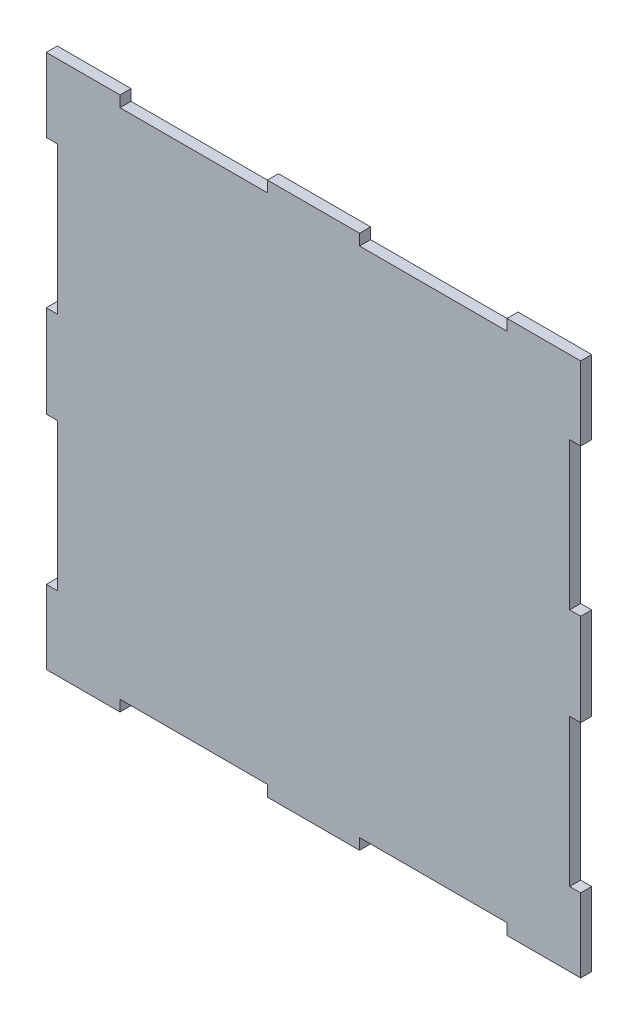
SolidWorks part; units mm, degrees
ref_plane "Front Plane" through (0, 0, 0) normal (0, 0, 1) x (1, 0, 0)
ref_plane "Top Plane" through (0, 0, 0) normal (0, 1, 0) x (1, 0, 0)
ref_plane "Right Plane" through (0, 0, 0) normal (1, 0, 0) x (0, 0, -1)
sketch "Sketch1" plane through (0, 0, 0) normal (0, 0, 1) x (1, 0, 0)
  line L1 (-72.5, 72.5) -> (72.5, 72.5)
  line L2 (-72.5, 72.5) -> (-72.5, -72.5)
  line L3 (-72.5, -72.5) -> (72.5, -72.5)
  line L4 (72.5, 72.5) -> (72.5, -72.5)
  line L5 (-72.5, 72.5) -> (72.5, -72.5) construction
  line L6 (-72.5, -72.5) -> (72.5, 72.5) construction
  point P0 (0, 0)
  dimension "D1" = 145
  dimension "D2" = 145
extrude "Boss-Extrude179" add sketch "Sketch1" along normal blind 3
sketch "Sketch2" plane through (0, 0, 3) normal (0, 0, 1) x (1, 0, 0)
  line L0 (-72.5, 0) -> (0, 0) construction
  line L1 (-72.5, 72.5) -> (-72.5, -72.5) construction
  line L2 (0, 0) -> (0, 72.5) construction
  line L3 (72.5, 72.5) -> (-72.5, 72.5) construction
  line L4 (-92.5, 52.5) -> (-92.5, -52.5) construction
  line L5 (-52.5, 72.5) -> (-12.5, 72.5)
  line L6 (-52.5, 72.5) -> (-52.5, 69.5)
  line L7 (-52.5, 69.5) -> (-12.5, 69.5)
  line L8 (-12.5, 72.5) -> (-12.5, 69.5)
  line L9 (12.5, 72.5) -> (52.5, 72.5)
  line L10 (12.5, 72.5) -> (12.5, 69.5)
  line L11 (12.5, 69.5) -> (52.5, 69.5)
  line L12 (52.5, 72.5) -> (52.5, 69.5)
  line L13 (-72.5, 52.5) -> (-69.5, 52.5)
  line L14 (-72.5, 52.5) -> (-72.5, 12.5)
  line L15 (-72.5, 12.5) -> (-69.5, 12.5)
  line L16 (-69.5, 52.5) -> (-69.5, 12.5)
  line L17 (-72.5, -12.5) -> (-69.5, -12.5)
  line L18 (-72.5, -12.5) -> (-72.5, -52.5)
  line L19 (-72.5, -52.5) -> (-69.5, -52.5)
  line L20 (-69.5, -12.5) -> (-69.5, -52.5)
  line L21 (-52.5, 92.5) -> (52.5, 92.5) construction
  line L22 (72.5, -72.5) -> (72.5, 72.5) construction
  line L23 (52.5, -72.5) -> (52.5, -69.5)
  line L24 (12.5, -69.5) -> (52.5, -69.5)
  line L25 (12.5, -72.5) -> (12.5, -69.5)
  line L26 (12.5, -72.5) -> (52.5, -72.5)
  line L27 (-12.5, -72.5) -> (-12.5, -69.5)
  line L28 (-52.5, -69.5) -> (-12.5, -69.5)
  line L29 (-52.5, -72.5) -> (-52.5, -69.5)
  line L30 (-52.5, -72.5) -> (-12.5, -72.5)
  line L31 (69.5, -12.5) -> (69.5, -52.5)
  line L32 (72.5, -52.5) -> (69.5, -52.5)
  line L33 (72.5, -12.5) -> (72.5, -52.5)
  line L34 (72.5, -12.5) -> (69.5, -12.5)
  line L35 (69.5, 52.5) -> (69.5, 12.5)
  line L36 (72.5, 12.5) -> (69.5, 12.5)
  line L37 (72.5, 52.5) -> (72.5, 12.5)
  line L38 (72.5, 52.5) -> (69.5, 52.5)
  point P28 (0, 0)
  point P29 (0, 92.5)
  point P30 (0, 0)
  point P31 (-92.5, 0)
  point P32 (0, 0)
  point P33 (0, 0)
  point P34 (0, 0)
  point P35 (0, 0)
  point P36 (0, 0)
  point P37 (52.5, 71)
  dimension "D1" = 3
  dimension "D2" = 40
  dimension "D3" = 20
  dimension "D4" = 20
  dimension "D5" = 20
  dimension "D6" = 20
extrude "Cut-Extrude1" cut sketch "Sketch2" against normal blind 3
